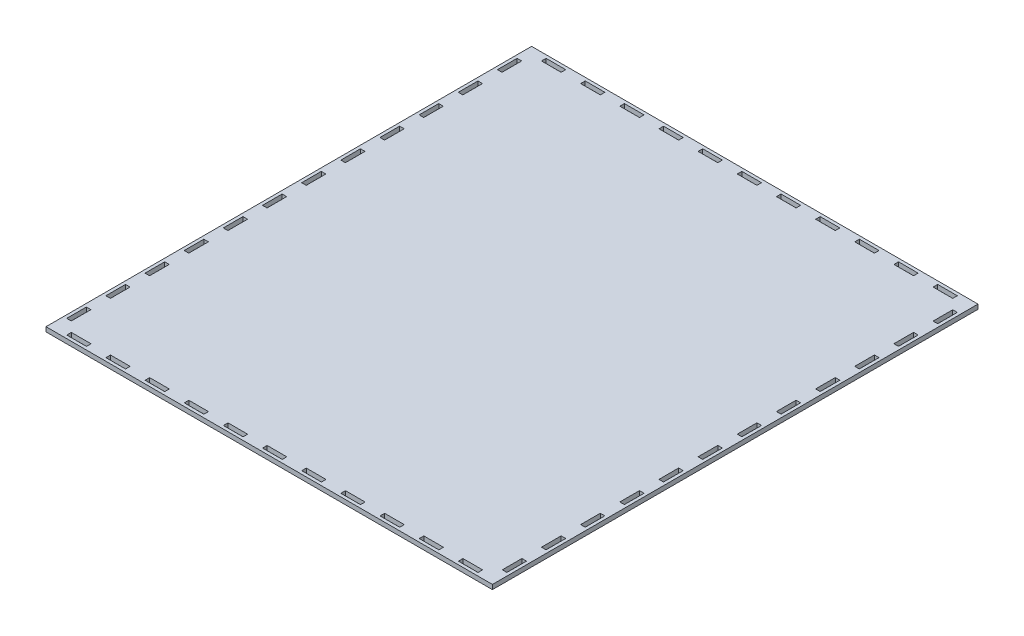
SolidWorks part; units mm, degrees
ref_plane "Спереди" through (0, 0, 0) normal (0, 0, 1) x (1, 0, 0)
ref_plane "Сверху" through (0, 0, 0) normal (0, 1, 0) x (1, 0, 0)
ref_plane "Справа" through (0, 0, 0) normal (1, 0, 0) x (0, 0, -1)
other "Configuration Table"
sketch "Sketch1" plane through (0, 0, 0) normal (0, 1, 0) x (1, 0, 0)
  line L1 (-285, -310) -> (285, -310)
  line L2 (-285, -310) -> (-285, 310)
  line L3 (-285, 310) -> (285, 310)
  line L4 (285, -310) -> (285, 310)
  line L5 (-285, -310) -> (285, 310) construction
  line L6 (-285, 310) -> (285, -310) construction
  line L9 (-212.5, 306) -> (-212.5, 300.15)
  line L10 (-262.5, 306) -> (-237.4, 306)
  line L11 (-262.5, 306) -> (-262.5, 300.15)
  line L12 (-262.5, 300.15) -> (-237.4, 300.15)
  line L13 (-237.4, 306) -> (-237.4, 300.15)
  line L14 (-212.5, 306) -> (-187.4, 306)
  line L15 (-187.4, 306) -> (-187.4, 300.15)
  line L16 (-212.5, 300.15) -> (-187.4, 300.15)
  line L17 (-162.5, 306) -> (-162.5, 300.15)
  line L18 (-162.5, 306) -> (-137.4, 306)
  line L19 (-137.4, 306) -> (-137.4, 300.15)
  line L20 (-162.5, 300.15) -> (-137.4, 300.15)
  line L21 (-112.5, 306) -> (-112.5, 300.15)
  line L22 (-112.5, 306) -> (-87.4, 306)
  line L23 (-87.4, 306) -> (-87.4, 300.15)
  line L24 (-112.5, 300.15) -> (-87.4, 300.15)
  line L25 (-62.5, 306) -> (-62.5, 300.15)
  line L26 (-62.5, 306) -> (-37.4, 306)
  line L27 (-37.4, 306) -> (-37.4, 300.15)
  line L28 (-62.5, 300.15) -> (-37.4, 300.15)
  line L29 (-12.5, 306) -> (-12.5, 300.15)
  line L30 (-12.5, 306) -> (12.6, 306)
  line L31 (12.6, 306) -> (12.6, 300.15)
  line L32 (-12.5, 300.15) -> (12.6, 300.15)
  line L33 (37.5, 306) -> (37.5, 300.15)
  line L34 (37.5, 306) -> (62.6, 306)
  line L35 (62.6, 306) -> (62.6, 300.15)
  line L36 (37.5, 300.15) -> (62.6, 300.15)
  line L37 (87.5, 306) -> (87.5, 300.15)
  line L38 (87.5, 306) -> (112.6, 306)
  line L39 (112.6, 306) -> (112.6, 300.15)
  line L40 (87.5, 300.15) -> (112.6, 300.15)
  line L41 (137.5, 306) -> (137.5, 300.15)
  line L42 (137.5, 306) -> (162.6, 306)
  line L43 (162.6, 306) -> (162.6, 300.15)
  line L44 (137.5, 300.15) -> (162.6, 300.15)
  line L45 (187.5, 306) -> (187.5, 300.15)
  line L46 (187.5, 306) -> (212.6, 306)
  line L47 (212.6, 306) -> (212.6, 300.15)
  line L48 (187.5, 300.15) -> (212.6, 300.15)
  line L49 (237.5, 306) -> (237.5, 300.15)
  line L50 (237.5, 306) -> (262.6, 306)
  line L51 (262.6, 306) -> (262.6, 300.15)
  line L52 (237.5, 300.15) -> (262.6, 300.15)
  line L53 (237.5, -300.15) -> (262.6, -300.15)
  line L54 (262.6, -306) -> (262.6, -300.15)
  line L55 (237.5, -306) -> (262.6, -306)
  line L56 (237.5, -306) -> (237.5, -300.15)
  line L57 (187.5, -300.15) -> (212.6, -300.15)
  line L58 (212.6, -306) -> (212.6, -300.15)
  line L59 (187.5, -306) -> (212.6, -306)
  line L60 (187.5, -306) -> (187.5, -300.15)
  line L61 (137.5, -300.15) -> (162.6, -300.15)
  line L62 (162.6, -306) -> (162.6, -300.15)
  line L63 (137.5, -306) -> (162.6, -306)
  line L64 (137.5, -306) -> (137.5, -300.15)
  line L65 (87.5, -300.15) -> (112.6, -300.15)
  line L66 (112.6, -306) -> (112.6, -300.15)
  line L67 (87.5, -306) -> (112.6, -306)
  line L68 (87.5, -306) -> (87.5, -300.15)
  line L69 (37.5, -300.15) -> (62.6, -300.15)
  line L70 (62.6, -306) -> (62.6, -300.15)
  line L71 (37.5, -306) -> (62.6, -306)
  line L72 (37.5, -306) -> (37.5, -300.15)
  line L73 (-12.5, -300.15) -> (12.6, -300.15)
  line L74 (12.6, -306) -> (12.6, -300.15)
  line L75 (-12.5, -306) -> (12.6, -306)
  line L76 (-12.5, -306) -> (-12.5, -300.15)
  line L77 (-62.5, -300.15) -> (-37.4, -300.15)
  line L78 (-37.4, -306) -> (-37.4, -300.15)
  line L79 (-62.5, -306) -> (-37.4, -306)
  line L80 (-62.5, -306) -> (-62.5, -300.15)
  line L81 (-112.5, -300.15) -> (-87.4, -300.15)
  line L82 (-87.4, -306) -> (-87.4, -300.15)
  line L83 (-112.5, -306) -> (-87.4, -306)
  line L84 (-112.5, -306) -> (-112.5, -300.15)
  line L85 (-162.5, -300.15) -> (-137.4, -300.15)
  line L86 (-137.4, -306) -> (-137.4, -300.15)
  line L87 (-162.5, -306) -> (-137.4, -306)
  line L88 (-162.5, -306) -> (-162.5, -300.15)
  line L89 (-212.5, -300.15) -> (-187.4, -300.15)
  line L90 (-187.4, -306) -> (-187.4, -300.15)
  line L91 (-212.5, -306) -> (-187.4, -306)
  line L92 (-237.4, -306) -> (-237.4, -300.15)
  line L93 (-262.5, -300.15) -> (-237.4, -300.15)
  line L94 (-262.5, -306) -> (-262.5, -300.15)
  line L95 (-262.5, -306) -> (-237.4, -306)
  line L96 (-212.5, -306) -> (-212.5, -300.15)
  line L97 (-281, 237.5) -> (-281, 212.4)
  line L98 (-281, 287.5) -> (-275.15, 287.5)
  line L99 (-281, 287.5) -> (-281, 262.4)
  line L100 (-281, 262.4) -> (-275.15, 262.4)
  line L101 (-275.15, 287.5) -> (-275.15, 262.4)
  line L102 (-281, 237.5) -> (-275.15, 237.5)
  line L103 (-275.15, 237.5) -> (-275.15, 212.4)
  line L104 (-281, 212.4) -> (-275.15, 212.4)
  line L105 (-281, 187.5) -> (-281, 162.4)
  line L106 (-281, 187.5) -> (-275.15, 187.5)
  line L107 (-275.15, 187.5) -> (-275.15, 162.4)
  line L108 (-281, 162.4) -> (-275.15, 162.4)
  line L109 (-281, 137.5) -> (-281, 112.4)
  line L110 (-281, 137.5) -> (-275.15, 137.5)
  line L111 (-275.15, 137.5) -> (-275.15, 112.4)
  line L112 (-281, 112.4) -> (-275.15, 112.4)
  line L113 (-281, 87.5) -> (-281, 62.4)
  line L114 (-281, 87.5) -> (-275.15, 87.5)
  line L115 (-275.15, 87.5) -> (-275.15, 62.4)
  line L116 (-281, 62.4) -> (-275.15, 62.4)
  line L117 (-281, 37.5) -> (-281, 12.4)
  line L118 (-281, 37.5) -> (-275.15, 37.5)
  line L119 (-275.15, 37.5) -> (-275.15, 12.4)
  line L120 (-281, 12.4) -> (-275.15, 12.4)
  line L121 (-281, -12.5) -> (-281, -37.6)
  line L122 (-281, -12.5) -> (-275.15, -12.5)
  line L123 (-275.15, -12.5) -> (-275.15, -37.6)
  line L124 (-281, -37.6) -> (-275.15, -37.6)
  line L125 (-281, -62.5) -> (-281, -87.6)
  line L126 (-281, -62.5) -> (-275.15, -62.5)
  line L127 (-275.15, -62.5) -> (-275.15, -87.6)
  line L128 (-281, -87.6) -> (-275.15, -87.6)
  line L129 (-281, -112.5) -> (-281, -137.6)
  line L130 (-281, -112.5) -> (-275.15, -112.5)
  line L131 (-275.15, -112.5) -> (-275.15, -137.6)
  line L132 (-281, -137.6) -> (-275.15, -137.6)
  line L133 (-281, -162.5) -> (-281, -187.6)
  line L134 (-281, -162.5) -> (-275.15, -162.5)
  line L135 (-275.15, -162.5) -> (-275.15, -187.6)
  line L136 (-281, -187.6) -> (-275.15, -187.6)
  line L137 (-281, -212.5) -> (-281, -237.6)
  line L138 (-281, -212.5) -> (-275.15, -212.5)
  line L139 (-275.15, -212.5) -> (-275.15, -237.6)
  line L140 (-281, -237.6) -> (-275.15, -237.6)
  line L141 (-281, -262.5) -> (-281, -287.6)
  line L142 (-281, -262.5) -> (-275.15, -262.5)
  line L143 (-275.15, -262.5) -> (-275.15, -287.6)
  line L144 (-281, -287.6) -> (-275.15, -287.6)
  line L145 (281, -287.5) -> (275.15, -287.5)
  line L146 (275.15, -262.4) -> (275.15, -287.5)
  line L147 (281, -262.4) -> (275.15, -262.4)
  line L148 (281, -262.4) -> (281, -287.5)
  line L149 (281, -237.5) -> (275.15, -237.5)
  line L150 (275.15, -212.4) -> (275.15, -237.5)
  line L151 (281, -212.4) -> (275.15, -212.4)
  line L152 (281, -212.4) -> (281, -237.5)
  line L153 (281, -187.5) -> (275.15, -187.5)
  line L154 (275.15, -162.4) -> (275.15, -187.5)
  line L155 (281, -162.4) -> (275.15, -162.4)
  line L156 (281, -162.4) -> (281, -187.5)
  line L157 (281, -137.5) -> (275.15, -137.5)
  line L158 (275.15, -112.4) -> (275.15, -137.5)
  line L159 (281, -112.4) -> (275.15, -112.4)
  line L160 (281, -112.4) -> (281, -137.5)
  line L161 (281, -87.5) -> (275.15, -87.5)
  line L162 (275.15, -62.4) -> (275.15, -87.5)
  line L163 (281, -62.4) -> (275.15, -62.4)
  line L164 (281, -62.4) -> (281, -87.5)
  line L165 (281, -37.5) -> (275.15, -37.5)
  line L166 (275.15, -12.4) -> (275.15, -37.5)
  line L167 (281, -12.4) -> (275.15, -12.4)
  line L168 (281, -12.4) -> (281, -37.5)
  line L169 (281, 12.5) -> (275.15, 12.5)
  line L170 (275.15, 37.6) -> (275.15, 12.5)
  line L171 (281, 37.6) -> (275.15, 37.6)
  line L172 (281, 37.6) -> (281, 12.5)
  line L173 (281, 62.5) -> (275.15, 62.5)
  line L174 (275.15, 87.6) -> (275.15, 62.5)
  line L175 (281, 87.6) -> (275.15, 87.6)
  line L176 (281, 87.6) -> (281, 62.5)
  line L177 (281, 112.5) -> (275.15, 112.5)
  line L178 (275.15, 137.6) -> (275.15, 112.5)
  line L179 (281, 137.6) -> (275.15, 137.6)
  line L180 (281, 137.6) -> (281, 112.5)
  line L181 (281, 162.5) -> (275.15, 162.5)
  line L182 (275.15, 187.6) -> (275.15, 162.5)
  line L183 (281, 187.6) -> (275.15, 187.6)
  line L184 (281, 187.6) -> (281, 162.5)
  line L185 (281, 212.5) -> (275.15, 212.5)
  line L186 (275.15, 237.6) -> (275.15, 212.5)
  line L187 (281, 237.6) -> (275.15, 237.6)
  line L188 (275.15, 287.6) -> (275.15, 262.5)
  line L189 (281, 262.5) -> (275.15, 262.5)
  line L190 (281, 287.6) -> (281, 262.5)
  line L191 (281, 287.6) -> (275.15, 287.6)
  line L192 (281, 237.6) -> (281, 212.5)
  point P0 (0, 0)
  dimension "D5" = 5.85
  dimension "D17" = 22.4
  dimension "D20" = 25.1
  dimension "D21" = 22.4
  dimension "D1" = 570
  dimension "D2" = 620
  dimension "D3" = 5.85
  dimension "D4" = 4
  dimension "D6" = 22.5
  dimension "D7" = 25.1
  dimension "D8" = 4
  dimension "D9" = 5.85
  dimension "D11" = 25.1
  dimension "D12" = 5.85
  dimension "D13" = 22.5
  dimension "D14" = 4
  dimension "D16" = 4
  dimension "D18" = 25.1
  dimension "D19" = 25.1
  dimension "D10" = 11
  dimension "D15" = 12
extrude "Boss-Extrude1" add sketch "Sketch1" along normal blind 5.8
